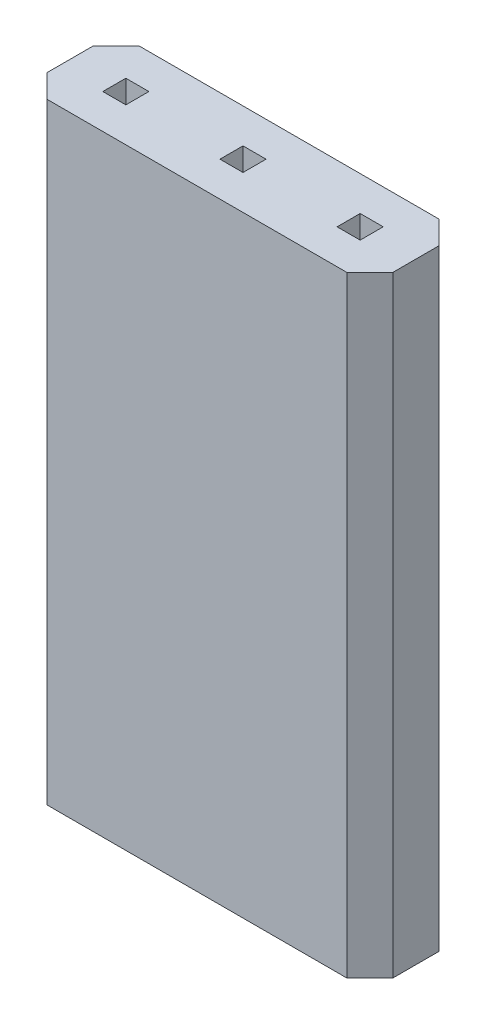
SolidWorks part; units mm, degrees
ref_plane "前视基准面" through (0, 0, 0) normal (0, 0, 1) x (1, 0, 0)
ref_plane "上视基准面" through (0, 0, 0) normal (0, 1, 0) x (1, 0, 0)
ref_plane "右视基准面" through (0, 0, 0) normal (1, 0, 0) x (0, 0, -1)
other "Configuration Table"
sketch "草图1" plane through (0, 0, 0) normal (0, 1, 0) x (1, 0, 0)
  line L1 (-3.75, 1) -> (3.75, 1)
  line L2 (-3.75, 1) -> (-3.75, -1)
  line L3 (-3.75, -1) -> (3.75, -1)
  line L4 (3.75, 1) -> (3.75, -1)
  line L5 (-3.75, 1) -> (3.75, -1) construction
  line L6 (-3.75, -1) -> (3.75, 1) construction
  point P0 (0, 0)
  dimension "D1" = 2
  dimension "D2" = 7.5
extrude "凸台-拉伸1" add sketch "草图1" along normal blind 13.25
sketch "草图2" plane through (0, 0, 0) normal (0, 1, 0) x (1, 0, 0)
  line L0 (2.29, 0.25) -> (2.29, -0.25)
  line L1 (-0.25, 0.25) -> (0.25, 0.25)
  line L2 (-0.25, 0.25) -> (-0.25, -0.25)
  line L3 (-0.25, -0.25) -> (0.25, -0.25)
  line L4 (0.25, 0.25) -> (0.25, -0.25)
  line L5 (-0.25, 0.25) -> (0.25, -0.25) construction
  line L6 (-0.25, -0.25) -> (0.25, 0.25) construction
  line L7 (2.29, 0.25) -> (2.79, 0.25)
  line L8 (2.79, 0.25) -> (2.79, -0.25)
  line L9 (2.29, -0.25) -> (2.79, -0.25)
  line L10 (-0.25, 0.25) -> (2.29, 0.25) construction
  line L11 (-2.79, 0.25) -> (-2.79, -0.25)
  line L12 (-2.79, 0.25) -> (-2.29, 0.25)
  line L13 (-2.29, 0.25) -> (-2.29, -0.25)
  line L14 (-2.79, -0.25) -> (-2.29, -0.25)
  line L15 (-0.25, 0.25) -> (-2.79, 0.25) construction
  point P0 (0, 0)
  dimension "D1" = 0.5
  dimension "D2" = 0.5
  dimension "D4" = 2.54
  dimension "D6" = 2.54
  dimension "D3" = 2
  dimension "D5" = 2
extrude "切除-拉伸1" cut sketch "草图2" against normal blind 7 from surface at 13.25 starting at face at (0, 13.25, 0)
sketch "草图3" plane through (0, 0, 0) normal (0, 1, 0) x (1, 0, 0)
  line L0 (-3.75, -1) -> (-3.25, -1)
  line L1 (-3.75, -1) -> (3.75, -1) construction
  line L2 (-3.25, -1) -> (-3.75, -0.5)
  line L3 (-3.75, 1) -> (-3.75, -1) construction
  line L4 (-3.75, -0.5) -> (-3.75, -1)
  line L5 (-3.75, 1) -> (-3.75, 0.5)
  line L6 (-3.75, 0.5) -> (-3.25, 1)
  line L7 (3.75, 1) -> (-3.75, 1) construction
  line L8 (-3.25, 1) -> (-3.75, 1)
  line L9 (3.75, -1) -> (3.75, -0.5)
  line L10 (3.75, -1) -> (3.75, 1) construction
  line L11 (3.75, -0.5) -> (3.25, -1)
  line L12 (3.25, -1) -> (3.75, -1)
  line L13 (3.75, 1) -> (3.75, 0.5)
  line L14 (3.75, 0.5) -> (3.25, 1)
  line L15 (3.25, 1) -> (3.75, 1)
  dimension "D1" = 0.5
  dimension "D2" = 0.5
  dimension "D3" = 0.5
  dimension "D4" = 0.5
  dimension "D5" = 0.5
  dimension "D6" = 0.5
  dimension "D7" = 0.5
  dimension "D8" = 0.5
extrude "切除-拉伸2" cut sketch "草图3" along normal through all contours L2 L4 L0 | L6 L8 L5 | L11 L12 L9 | L15 L14 L13
